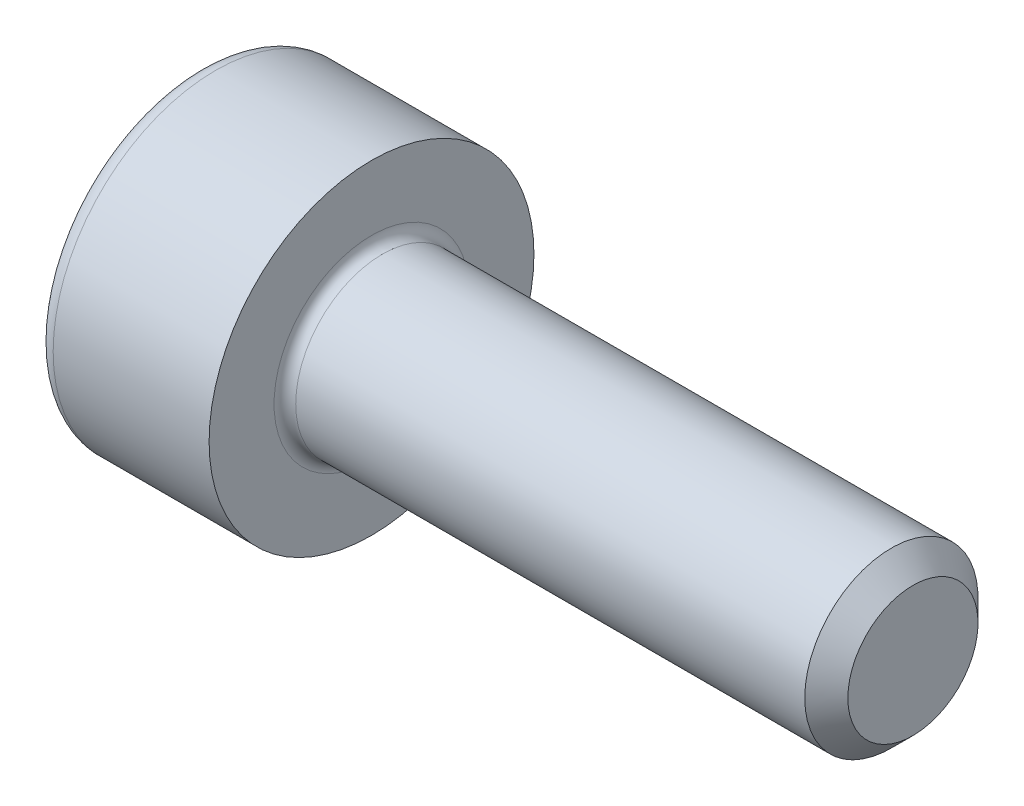
SolidWorks part; units mm, degrees
ref_plane "Plane1" through (0, 0, 0) normal (0, 0, 1) x (1, 0, 0)
ref_plane "Plane2" through (0, 0, 0) normal (0, 1, 0) x (1, 0, 0)
ref_plane "Plane3" through (0, 0, 0) normal (1, 0, 0) x (0, 0, -1)
sketch "BodySke" plane through (0, 0, 0) normal (0, 0, 1) x (1, 0, 0)
  line L0 (0, 0) -> (0, 1.5)
  line L1 (0, 1.5) -> (1.6, 1.5)
  line L2 (1.6, 1.5) -> (1.6, 0.8)
  line L3 (1.6, 0.8) -> (6.401, 0.8)
  line L4 (6.6, 0.601) -> (6.6, 0)
  line L5 (6.6, 0) -> (0, 0)
  line L6 (-31.75, 0) -> (127, 0) construction
  line L8 (6.6, 0.601) -> (6.401, 0.8)
  line L10 (6.6, -0.601) -> (6.401, -0.8) construction
  line L11 (1.95, 9.525) -> (1.95, 3.175) construction
  line L12 (1.6, 9.525) -> (1.6, 3.175) construction
  line L13 (-53.4, 9.525) -> (-53.4, 3.175) construction
  dimension "Diameter" = 1.6
  dimension "Head_ht" = 1.6
  dimension "Length" = 5
  dimension "Body_ch_ang" = 45
  dimension "Head_dia" = 3
  dimension "Minor_dia" = 1.202
  dimension "Advance" = 0.35
  dimension "Thread_nom" = 5
  dimension "Thread_length" = 60
revolve "Base-Revolve" add sketch "BodySke"
cosmetic thread "ThreadCosmetic"
fillet "Fillet1" radius 0.1 1 edges at (1.6, 0, 0.8)
fillet "Fillet2" radius 0.16 1 edges at (0, 0, 1.5)
sketch "Sketch2" plane through (0, 0, 0) normal (0, 0, 1) x (1, 0, 0)
  line L0 (0, 0.76) -> (0.7, 0.76)
  line L1 (0.7, 0.76) -> (1.1388, 0)
  line L2 (-31.75, 0) -> (127, 0) construction
  line L3 (1.1388, 0) -> (0, 0)
  line L4 (0, 0) -> (0, 0.76)
  line L6 (0, 0) -> (47.625, 0) construction
  dimension "D1" = 0.76
  dimension "D2" = 60
  dimension "Depth" = 0.7
revolve "Hex-PreBroach" cut sketch "Sketch2" angle 360 about L6
sketch "Sketch3" plane through (0, 0, 0) normal (-1, 0, 0) x (0, 0.5, 0.866)
  line L0 (0.4388, 0.76) -> (-0.4388, 0.76)
  line L1 (-0.4388, 0.76) -> (-0.8776, 0)
  line L2 (0.4388, 0.76) -> (0.8776, 0)
  line L3 (0.4388, -0.76) -> (0.8776, 0)
  line L4 (0.4388, -0.76) -> (-0.4388, -0.76)
  line L5 (-0.4388, -0.76) -> (-0.8776, 0)
  dimension "D1" = 0.76
  dimension "D2" = 0.76
  dimension "Hex_size" = 1.52
extrude "Hex" cut sketch "Sketch3" against normal blind 0.7
sketch "ThdSchSke" plane through (0, 0, 0) normal (0, 0, 1) x (1, 0, 0)
  line L0 (2.65, -0.601) -> (2.5107, -0.8)
  line L1 (2.65, -0.601) -> (2.7893, -0.8)
  line L2 (2.7893, -0.8) -> (2.7893, -1)
  line L3 (-3.175, 0) -> (5.1513, 0) construction
  line L4 (0, 1.34) -> (0, -1.34) construction
  line L5 (2.7893, -1) -> (2.5107, -1)
  line L6 (2.5107, -1) -> (2.5107, -0.8)
  dimension "Thread_minor" = 1.202
  dimension "Diameter" = 1.6
  dimension "Start" = 2.65
  dimension "SideAngle" = 55
  dimension "VeeAngle" = 70
  dimension "Overcut" = 2
revolve "ThreadSchematic" [suppressed] cut sketch "ThdSchSke" angle 360 about L3
pattern_linear "ThdSchPat" [suppressed]
equation "\"D2@Sketch3\" = \"Hex_size@Sketch3\" / 2"
equation "\"D1@Sketch3\" = \"Hex_size@Sketch3\" / 2"
equation "\"D1@Sketch2\" = \"Hex_size@Sketch3\" / 2"
equation "\"Thread_minor@ThreadCosmetic\"  =  \"Minor_dia@BodySke\""
equation "\"Depth@Sketch2\" =  \"Key_eng@Hex\""
equation "\"Thread_length@ThreadCosmetic\" = ((sgn( (\"Length@BodySke\" - \"Advance@BodySke\" * 3.0) - \"Thread_nom@BodySke\" )-1)*( (\"Length@BodySke\" - \"Advance@BodySke\" * 3.0) - \"Thread_nom@BodySke\" ))/-2+ \"Thread_nom@BodySke\""
equation "\"Thread_minor@ThdSchSke\" = \"Minor_dia@BodySke\""
equation "\"Diameter@ThdSchSke\" = \"Diameter@BodySke\""
equation "\"Overcut@ThdSchSke\" = \"Diameter@BodySke\" * 1.25"
equation "\"Start@ThdSchSke\" = \"Head_ht@BodySke\" + \"Length@BodySke\" - \"Thread_length@ThreadCosmetic\"  '---Non-countersunk---"
equation "\"Num_threads@ThdSchPat\" = int( \"Thread_length@ThreadCosmetic\" / \"Advance@BodySke\" + 0.999 )  + 1"
equation "\"Advance@ThdSchPat\" = \"Thread_length@ThreadCosmetic\" /  (\"Num_threads@ThdSchPat\" - 1) 'relax it"
equation "\"Num_threads@ThdSchPat\" = \"Num_threads@ThdSchPat\" - sgn( \"Num_threads@ThdSchPat\" - 1) '---chamfered tips only---"
